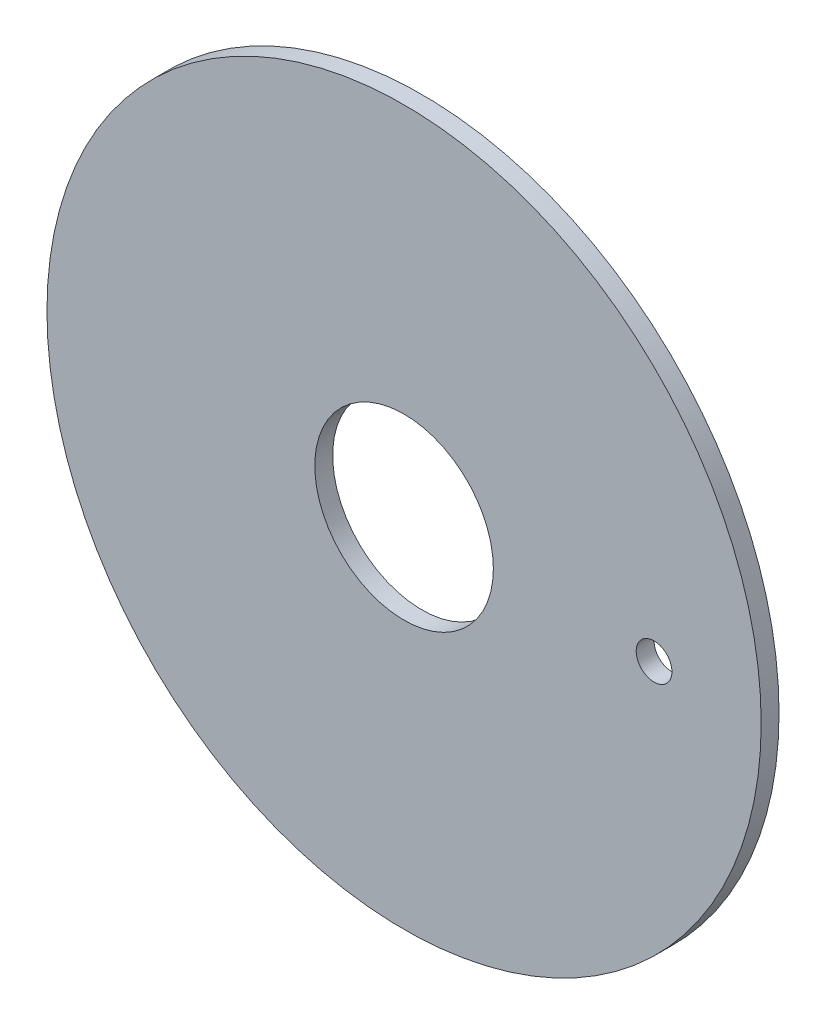
SolidWorks part; units mm, degrees
ref_plane "Front Plane" through (0, 0, 0) normal (0, 0, 1) x (1, 0, 0)
ref_plane "Top Plane" through (0, 0, 0) normal (0, 1, 0) x (1, 0, 0)
ref_plane "Right Plane" through (0, 0, 0) normal (1, 0, 0) x (0, 0, -1)
sketch "Sketch1" plane through (0, 0, 0) normal (0, 0, 1) x (1, 0, 0)
  circle A0 centre (0, 0) radius 100
  circle A1 centre (0, 0) radius 25
  circle A2 centre (0, 0) radius 70 construction
  circle A3 centre (70, 0) radius 5
  dimension "D1" = 50
  dimension "D2" = 200
  dimension "D3" = 140
  dimension "D4" = 10
extrude "Boss-Extrude1" add sketch "Sketch1" along normal blind 5
